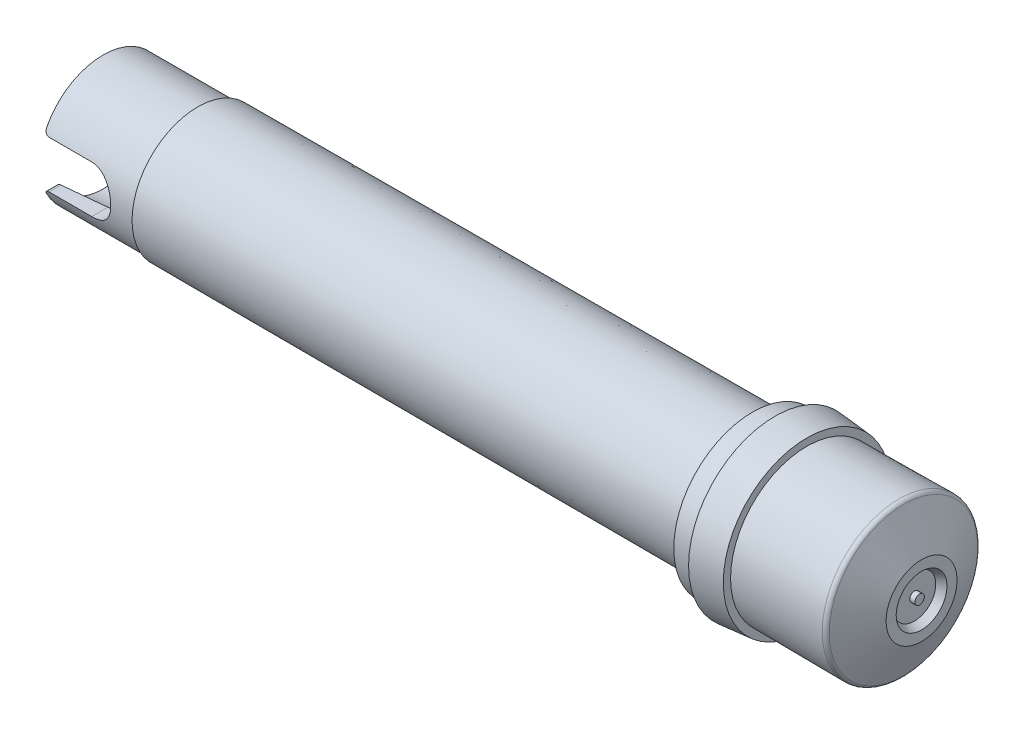
SolidWorks part; units mm, degrees
ref_plane "Plano frontal" through (0, 0, 0) normal (0, 0, 1) x (1, 0, 0)
ref_plane "Plano superior" through (0, 0, 0) normal (0, 1, 0) x (1, 0, 0)
ref_plane "Plano direito" through (0, 0, 0) normal (1, 0, 0) x (0, 0, -1)
sketch "Esboço1" plane through (0, 0, 0) normal (0, 0, 1) x (1, 0, 0)
  line L0 (0, 0) -> (34.6, 0) construction
  line L1 (0, 2.2325) -> (0, 2.675)
  line L3 (0, 2.675) -> (4, 2.675)
  line L4 (4, 2.675) -> (4, 2.775)
  line L6 (28.4, 3.325) -> (27.45, 3.325)
  line L7 (28.4, 3.325) -> (28.4, 3.65)
  line L8 (28.4, 3.65) -> (29.75, 3.5319)
  line L9 (29.75, 3.5319) -> (29.75, 3.225)
  line L10 (29.75, 3.225) -> (33.6532, 3.254)
  line L11 (33.8359, 3.1386) -> (34.6, 1.5)
  line L12 (34.6, 1.5) -> (34.6, 1.0732)
  line L13 (34.6, 0) -> (34.6, 7.2649) construction
  line L14 (34.6, 1.0732) -> (34.3, 0.9)
  line L15 (34.3, 0.9) -> (34.3, 0.2)
  line L16 (34.3, 0.2) -> (34.5176, 0.2)
  line L17 (34.5176, 0.2) -> (34.5176, 0)
  line L18 (3, 1.92) -> (33.7, 1.6521)
  line L19 (3, 1.92) -> (3, 1.97)
  line L20 (3, 1.97) -> (0, 2.2325)
  line L21 (4, 2.775) -> (27.45, 2.825)
  line L22 (33.07, 0) -> (33.7, 0) construction
  line L23 (27.45, 3.325) -> (27.45, 2.825)
  line L25 (28.4, 3.65) -> (30.998, 3.65) construction
  line L28 (33.7, 0) -> (34.5176, 0)
  line L29 (34.6, 1.0732) -> (34.6, 0) construction
  line L30 (33.7, 0) -> (33.7, 1.6521)
  arc A0 (33.6532, 3.254) -> (33.8359, 3.1386) centre (33.6547, 3.054) cw
  point P17 (33.7816, 3.255)
  dimension "D20" = 0.2
  dimension "D35" = 0.95
  dimension "D34" = 6.65
  dimension "D38" = 0.8184
  dimension "D26" = 5
  dimension "D1" = 34.6
  dimension "D4" = 3.84
  dimension "D5" = 5.55
  dimension "D6" = 4
  dimension "D7" = 5.35
  dimension "D8" = 28.4
  dimension "D9" = 5
  dimension "D10" = 7.3
  dimension "D12" = 5.65
  dimension "D14" = 7.0638
  dimension "D15" = 1.35
  dimension "D16" = 6.45
  dimension "D17" = 6.51
  dimension "D18" = 3
  dimension "D19" = 25
  dimension "D21" = 1.8
  dimension "D22" = 0.3
  dimension "D23" = 30
  dimension "D24" = 0.4
  dimension "D25" = 0.2176
  dimension "D27" = 3.3042
  dimension "D28" = 3
  dimension "D29" = 33.7
  dimension "D30" = 3.94
  dimension "D31" = 0.5
sketch "Esboço2" plane through (0, 0, 0) normal (0, 0, 1) x (1, 0, 0)
  line L0 (0, 1) -> (0, -1)
  line L1 (0, 2.2325) -> (0, 2.675) construction
  line L2 (0, 1) -> (2, 1)
  line L3 (2, -1) -> (0, -1)
  arc A0 (2, 1) -> (2, -1) centre (2, 0) cw
  point P0 (0, 0)
  dimension "D2" = 1
  dimension "D3" = 3
  dimension "D1" = 2
revolve "Revolução1" add sketch "Esboço1" angle 360 about L0
extrude "Extrusão1" cut sketch "Esboço2" against normal mid plane 10
fillet "Filete1" radius 0.1 1 edges at (33.7, 0, 1.6521)
fillet "Filete2" radius 0.2 4 edges at (0, -1, -2.2385) (0, -1, 2.2385) (0, 1, -2.2385) (0, 1, 2.2385)
fillet "Filete3" radius 0.03 1 edges at (3, 0, 1.92)
scale "MOLDE" [suppressed]
